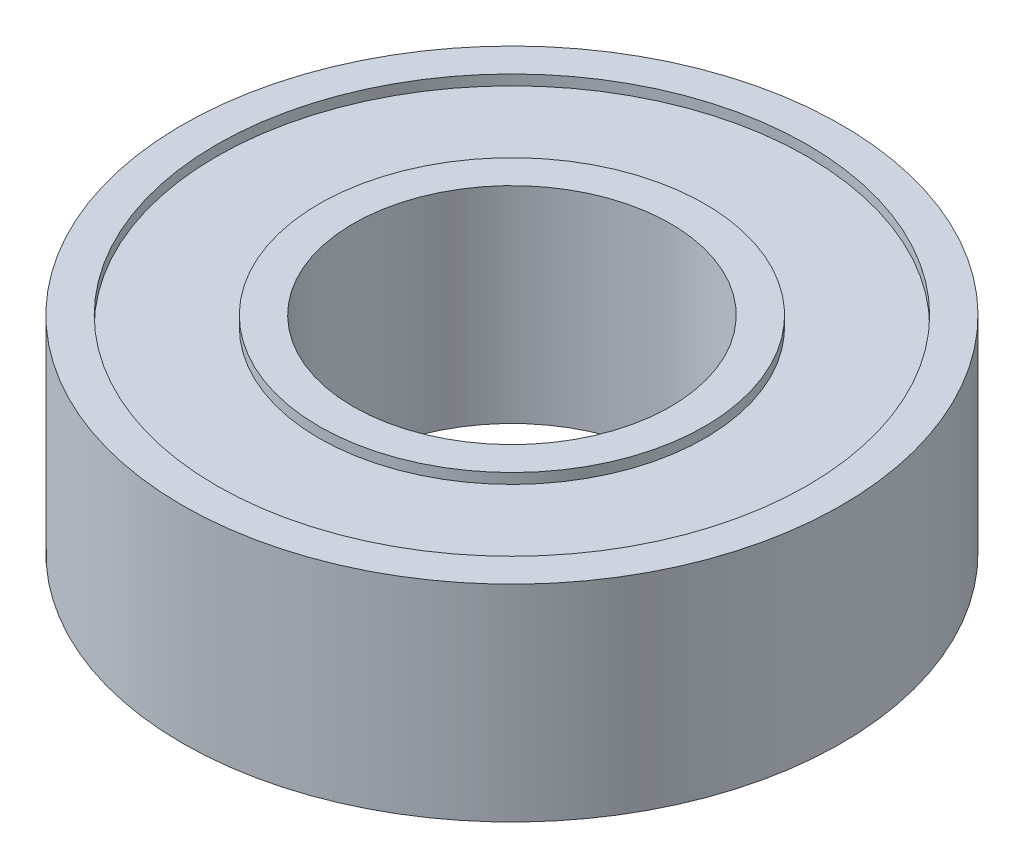
SolidWorks part; units mm, degrees
ref_plane "Спереди" through (0, 0, 0) normal (0, 0, 1) x (1, 0, 0)
ref_plane "Сверху" through (0, 0, 0) normal (0, 1, 0) x (1, 0, 0)
ref_plane "Справа" through (0, 0, 0) normal (1, 0, 0) x (0, 0, -1)
sketch "Эскиз1" plane through (0, 0, 0) normal (0, 1, 0) x (1, 0, 0)
  circle A0 centre (0, 0) radius 3.85
  circle A1 centre (0, 0) radius 8
  dimension "D1" = 7.7
  dimension "D2" = 16
extrude "Бобышка-Вытянуть1" add sketch "Эскиз1" along normal mid plane 5
sketch "Эскиз2" plane through (0, 2.5, 0) normal (0, 1, 0) x (1, 0, 0)
  circle A0 centre (0, 0) radius 4.68
  circle A1 centre (0, 0) radius 7.17
  circle A2 centre (0, 0) radius 3.85 construction
  circle A3 centre (0, 0) radius 8 construction
  dimension "D1" = 0.83
  dimension "D2" = 0.83
extrude "Вырез-Вытянуть1" cut sketch "Эскиз2" against normal blind 0.25
mirror "Зеркальное отражение1" about plane through (0, 0, 0) normal (0, 1, 0) of "Вырез-Вытянуть1"
equation "\"motor_diameter\"= 30"
equation "\"mm_diameter\"= IIF ( \"motor_diameter\" < 34 , 41 , \"motor_diameter\" + 8 )"
equation "\"upper_shafts_diameter\"= 5"
equation "\"upper_shats_length\"= 180"
equation "\"upper_bearing_d1\"= 10"
equation "\"upper_bearing_d2\"= 5"
equation "\"upper_bearing_h\"= 15"
equation "\"lower_shafts_diameter\"= 5"
equation "\"lower_shafts_length\"= 180"
equation "\"lower_bearing_d1\"= 10"
equation "\"lower_bearing_d2\"= 5"
equation "\"lower_bearing_h\"= 15"
equation "\"print_offset\"= 0.5"
equation "\"bh_screws_d\"= 2"
equation "\"bh_screws_h\"= 20"
equation "\"bh_screws_hh_d\"= 3.4"
equation "\"bh_screws_hh_h\"= 2"
equation "\"bh_nut_d\"= 3.8"
equation "\"bh_nut_h\"= 2"
equation "\"motor_screws_d\"= 3"
equation "\"motor_screws_h\"= 16"
equation "\"motor_screws_hh_d\"= 5.5"
equation "\"motor_screws_hh_h\"= 3"
equation "\"plate_hole_distance\"= 25.4"
equation "\"plate_screws_d\"= 6.5"
equation "\"shafts_diameter\"= IIF ( \"mm_diameter\" < 42 , 42 + 8 , \"mm_diameter\" + 8 )"
equation "\"central_hole_diameter\"= 8"
equation "\"bh_thikness\"= 4"
equation "\"ends_screws_d\"= 4"
equation "\"ends_screws_h\"= 16"
equation "\"ends_screws_hh_d\"= 6.7"
equation "\"ends_screws_hh_h\"= 4.1"
equation "\"ends_nut_d\"= 6.8"
equation "\"ends_nut_h\"= 3"
equation "\"system_radius\" = ( \"shafts_diameter\" + 12 + \"bh_thikness\" / 2 ) / 2"
equation "\"encoder_distance\"= \"system_radius\" + 4"
equation "\"tape_position\"= \"encoder_distance\" - 2 + 3.9 + 1.7 / 2"
equation "\"radial_bearing_d1\"= 7.7"
equation "\"radial_bearing_d2\"= 16"
equation "\"radial_bearing_h\"= 5"
equation "\"D1@Эскиз1\"=\"radial_bearing_d1\""
equation "\"D2@Эскиз1\"=\"radial_bearing_d2\""
equation "\"D1@Бобышка-Вытянуть1\"=\"radial_bearing_h\""
equation "\"D1@Эскиз2\"=(\"radial_bearing_d2\"-\"radial_bearing_d1\")*0.1"
equation "\"D2@Эскиз2\"=\"D1@Эскиз2\""
equation "\"D1@Вырез-Вытянуть1\"=\"radial_bearing_h\"*0.05"
